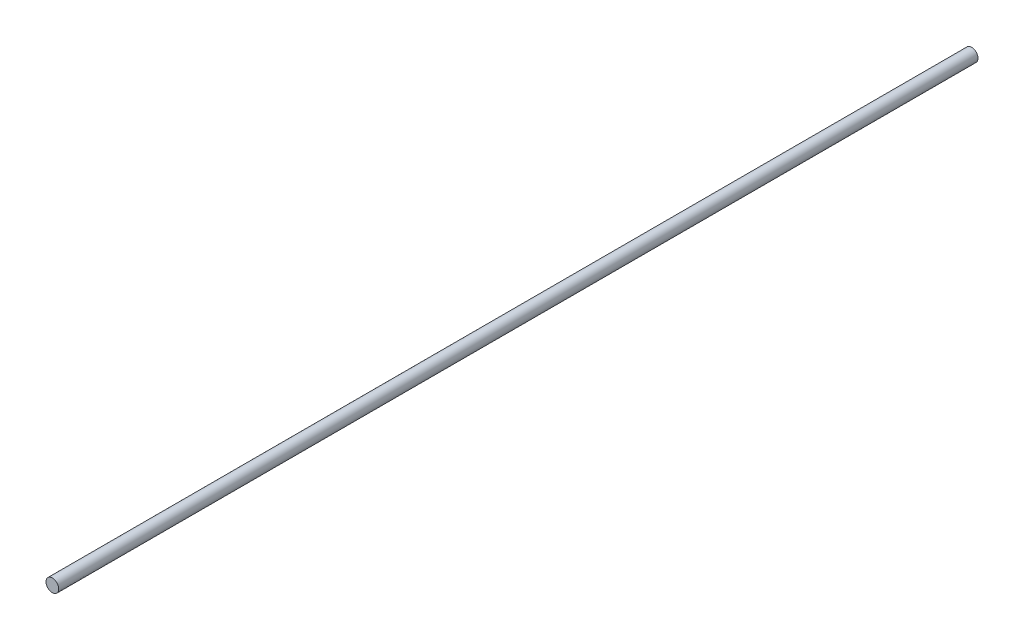
SolidWorks part; units mm, degrees
ref_plane "Front Plane" through (0, 0, 0) normal (0, 0, 1) x (1, 0, 0)
ref_plane "Top Plane" through (0, 0, 0) normal (0, 1, 0) x (1, 0, 0)
ref_plane "Right Plane" through (0, 0, 0) normal (1, 0, 0) x (0, 0, -1)
sketch "Sketch1" plane through (0, 0, 0) normal (0, 0, 1) x (1, 0, 0)
  circle A0 centre (0, 0) radius 1.4111
extrude "Boss-Extrude1" add sketch "Sketch1" along normal blind 203.2
